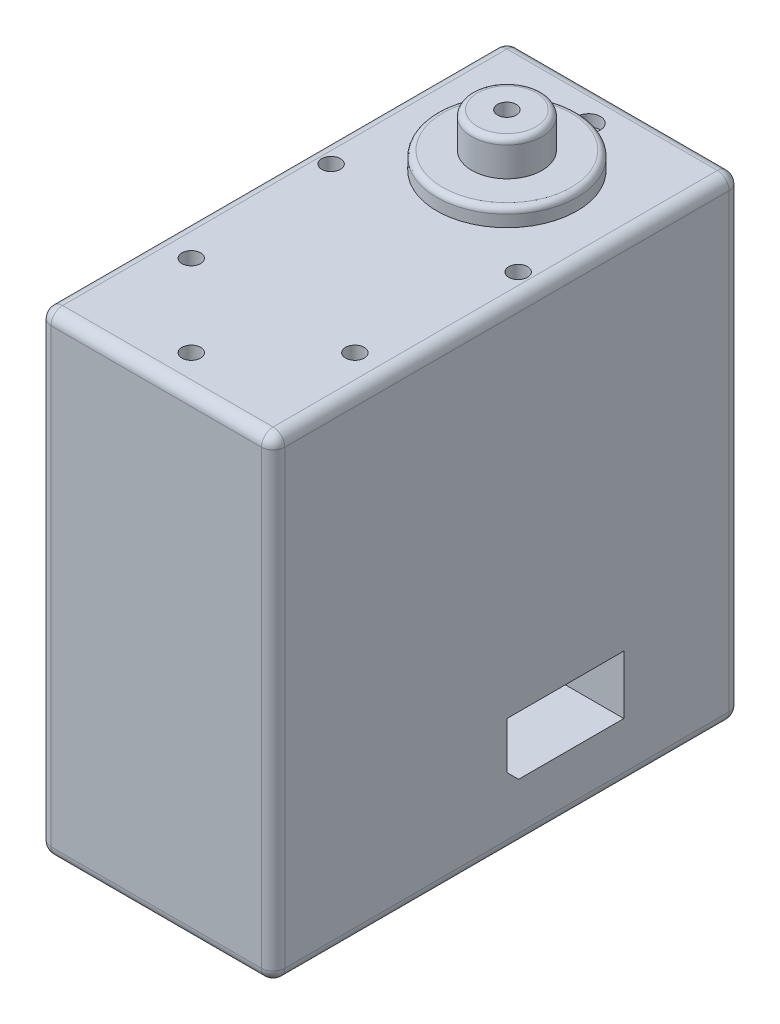
SolidWorks part; units mm, degrees
ref_plane "前视基准面" through (0, 0, 0) normal (0, 0, 1) x (1, 0, 0)
ref_plane "上视基准面" through (0, 0, 0) normal (0, 1, 0) x (1, 0, 0)
ref_plane "右视基准面" through (0, 0, 0) normal (1, 0, 0) x (0, 0, -1)
sketch "草图1" plane through (0, 0, 0) normal (1, 0, 0) x (0, 0, -1)
  line L1 (-20, 20.3) -> (20, 20.3)
  line L2 (-20, 20.3) -> (-20, -20.3)
  line L3 (-20, -20.3) -> (20, -20.3)
  line L4 (20, 20.3) -> (20, -20.3)
  dimension "D1" = 40
  dimension "D2" = 40.6
  dimension "D3" = 20.3
  dimension "D4" = 20
extrude "凸台-拉伸1" add sketch "草图1" along normal mid plane 20
sketch "草图2" plane through (0, 20.3, 0) normal (0, 1, 0) x (1, 0, 0)
  line L0 (10, 20) -> (-10, 20) construction
  line L1 (10, 20) -> (10, -20) construction
  circle A0 centre (0, 10) radius 6
  dimension "D1" = 12
  dimension "D2" = 10
  dimension "D3" = 10
extrude "凸台-拉伸2" add sketch "草图2" along normal blind 1.5
sketch "草图3" plane through (0, 21.8, 0) normal (0, 1, 0) x (1, 0, 0)
  circle A0 centre (0, 10) radius 3
  dimension "D1" = 6
extrude "凸台-拉伸3" add sketch "草图3" along normal blind 3
mirror "镜向1" about plane through (0, 0, 0) normal (0, 1, 0) of "凸台-拉伸3", "凸台-拉伸2"
sketch "草图6" plane through (0, -20.3, 0) normal (0, -1, 0) x (1, 0, 0)
  line L0 (10, 20) -> (10, -20) construction
  line L1 (10, -20) -> (-10, -20) construction
  circle A0 centre (7.5, -17.5) radius 1
  dimension "D1" = 2
  dimension "D2" = 2.5
  dimension "D3" = 2.5
hole_wizard "M2 螺纹孔1" positions "3D草图1" profile "草图7" tap size "M2" standard "GB"
sketch3d "3D草图1"
  point P0 (7.5, -20.3, -17.5)
sketch "草图7" plane through (7.5, -20.3, -17.5) normal (1, 0, 0) x (0, 0, -1)
  line L0 (0, 0) -> (0, 5.6807)
  line L1 (0, 5.6807) -> (0.8, 5.2)
  line L2 (0.8, 5.2) -> (0.8, 0)
  line L5 (0.8, 0) -> (0, 0)
  line L10 (0, 5.6807) -> (-0.8, 5.2) construction
  line L11 (0, -6.35) -> (0, 107.95) construction
  dimension "螺纹孔钻头直径" = 1.6
  dimension "螺纹孔钻头深度" = 5.2
  dimension "导头角度" = 118
cosmetic thread "孔螺蚊线1" parameters "D1"=4, "D2"=2
pattern_linear "阵列(线性)1" count 2 spacing 20 along (0, 0, 1) of "M2 螺纹孔1"
pattern_linear "阵列(线性)2" count 2 spacing 35 along (0, 0, 1) of "M2 螺纹孔1"
mirror "镜向2" about plane through (0, 0, 0) normal (1, 0, 0) of "阵列(线性)1", "阵列(线性)2", "M2 螺纹孔1"
sketch "草图8" plane through (0, 20.3, 0) normal (0, 1, 0) x (1, 0, 0)
  line L0 (10, -20) -> (-10, -20) construction
  line L1 (10, 20) -> (10, -20) construction
  circle A0 centre (0, -17) radius 1
  circle A1 centre (7, -10) radius 1
  circle A2 centre (-7, -10) radius 1
  circle A3 centre (-8, 2.9615) radius 1
  circle A4 centre (8, 2.9615) radius 1
  dimension "D1" = 2
  dimension "D2" = 3
  dimension "D3" = 10
  dimension "D4" = 2
  dimension "D5" = 2
  dimension "D6" = 14
  dimension "D7" = 7
  dimension "D8" = 7
  dimension "D9" = 7
  dimension "D10" = 2
  dimension "D11" = 2
  dimension "D12" = 16
  dimension "D13" = 8
  dimension "D14" = 13
  dimension "D15" = 13
hole_wizard "M2 螺纹孔2" positions "3D草图2" profile "草图9" tap size "M2" standard "GB"
sketch3d "3D草图2"
  point P0 (0, 20.3, 17)
  point P4 (-7, 20.3, 10)
  point P7 (7, 20.3, 10)
  point P10 (-8, 20.3, -2.9615)
  point P13 (8, 20.3, -2.9615)
sketch "草图9" plane through (0, 20.3, 17) normal (1, 0, 0) x (0, 0, 1)
  line L0 (0, 0) -> (0, 5.6807)
  line L1 (0, 5.6807) -> (0.8, 5.2)
  line L2 (0.8, 5.2) -> (0.8, 0)
  line L5 (0.8, 0) -> (0, 0)
  line L10 (0, 5.6807) -> (-0.8, 5.2) construction
  line L11 (0, -6.35) -> (0, 107.95) construction
  dimension "螺纹孔钻头直径" = 1.6
  dimension "螺纹孔钻头深度" = 5.2
  dimension "导头角度" = 118
cosmetic thread "孔螺蚊线2" parameters "D1"=4, "D2"=2
cosmetic thread "孔螺蚊线3" parameters "D1"=4, "D2"=2
cosmetic thread "孔螺蚊线4" parameters "D1"=4, "D2"=2
cosmetic thread "孔螺蚊线5" parameters "D1"=4, "D2"=2
cosmetic thread "孔螺蚊线6" parameters "D1"=4, "D2"=2
fillet "圆角1" radius 1 12 edges at (0, 20.3, 20) (10, 0, 20) (0, -20.3, 20) (-10, 0, 20) (-10, 20.3, 0) (-10, -20.3, 0) (10, -20.3, 0) (10, 20.3, 0) (0, -20.3, -20) (-10, 0, -20) (0, 20.3, -20) (10, 0, -20)
fillet "圆角3" radius 0.5 1 edges at (0, 21.8, -4)
fillet "圆角4" radius 0.5 2 edges at (0, -24.8, -7) (0, 24.8, -7)
sketch "草图10" plane through (0, 24.8, 0) normal (0, 1, 0) x (1, 0, 0)
  circle A0 centre (0, 10) radius 1
  dimension "D1" = 2
hole_wizard "M2 螺纹孔3" positions "3D草图3" profile "草图11" tap size "M2" standard "GB"
sketch3d "3D草图3"
  point P0 (0, 24.8, -10)
sketch "草图11" plane through (0, 24.8, -10) normal (1, 0, 0) x (0, 0, 1)
  line L0 (0, 0) -> (0, 5.6807)
  line L1 (0, 5.6807) -> (0.8, 5.2)
  line L2 (0.8, 5.2) -> (0.8, 0)
  line L5 (0.8, 0) -> (0, 0)
  line L10 (0, 5.6807) -> (-0.8, 5.2) construction
  line L11 (0, -6.35) -> (0, 107.95) construction
  dimension "螺纹孔钻头直径" = 1.6
  dimension "螺纹孔钻头深度" = 5.2
  dimension "导头角度" = 118
cosmetic thread "孔螺蚊线7" parameters "D1"=4, "D2"=2
sketch "草图12" plane through (0, 20.3, 0) normal (0, 1, 0) x (1, 0, 0)
  circle A0 centre (0, 17) radius 1
  circle A1 centre (0, 10) radius 5.5 construction
  dimension "D1" = 2
  dimension "D2" = 7
extrude "切除-拉伸2" cut sketch "草图12" against normal blind 1
sketch "草图13" plane through (-10, 0, 0) normal (-1, 0, 0) x (0, 0, 1)
  line L0 (19, -20.3) -> (-19, -20.3) construction
  line L1 (-10, -10.3) -> (0, -10.3)
  line L2 (-10, -10.3) -> (-10, -15.3)
  line L3 (-10, -15.3) -> (0, -15.3)
  line L4 (0, -10.3) -> (0, -15.3)
  line L5 (-20, -19.3) -> (-20, 19.3) construction
  dimension "D1" = 10
  dimension "D2" = 5
  dimension "D3" = 10
  dimension "D4" = 10
extrude "切除-拉伸3" cut sketch "草图13" against normal blind 5
chamfer "倒角1" distance 1 angle 45 1 edges at (-7.5, -15.3, 0)
mirror "镜向3" about plane through (0, 0, 0) normal (1, 0, 0) of "切除-拉伸3", "倒角1"
